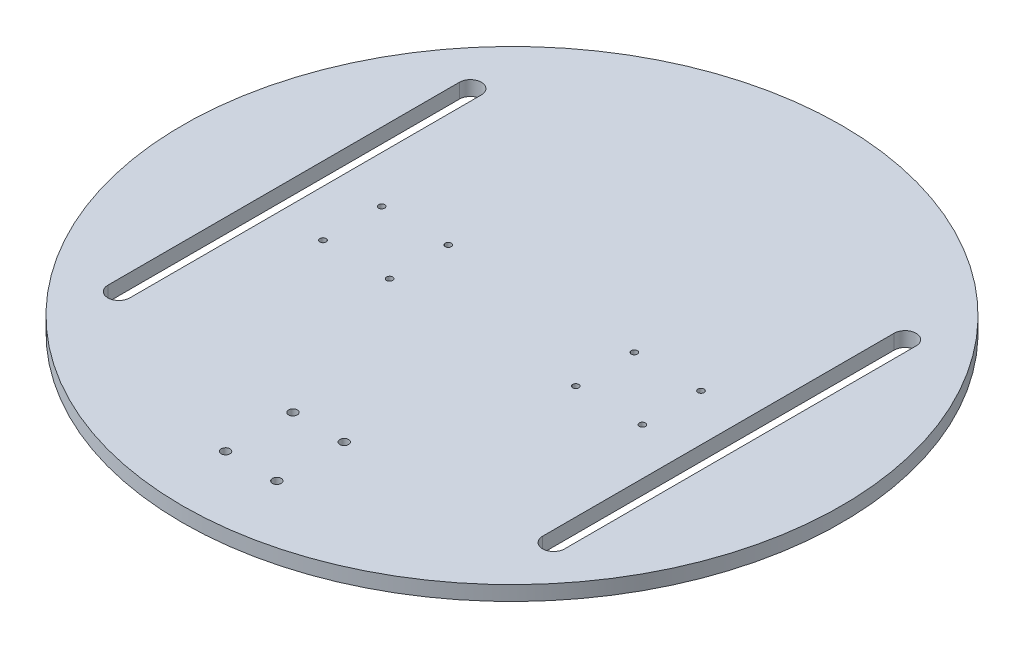
SolidWorks part; units mm, degrees
ref_plane "Front Plane" through (0, 0, 0) normal (0, 0, 1) x (1, 0, 0)
ref_plane "Top Plane" through (0, 0, 0) normal (0, 1, 0) x (1, 0, 0)
ref_plane "Right Plane" through (0, 0, 0) normal (1, 0, 0) x (0, 0, -1)
sketch "Sketch1" plane through (0, 0, 0) normal (0, 1, 0) x (1, 0, 0)
  line L0 (0, 225) -> (0, -225) construction
  line L1 (-225, 0) -> (225, 0) construction
  line L2 (-148.4069, 120) -> (-148.4069, -120) construction
  line L3 (-148.4069, -120) -> (-148.4069, 120) construction
  line L4 (-155.9069, -120) -> (-155.9069, 120)
  line L5 (-140.9069, -120) -> (-140.9069, 120)
  line L6 (148.4069, -120) -> (148.4069, 120) construction
  line L7 (155.9069, -120) -> (155.9069, 120)
  line L8 (140.9069, -120) -> (140.9069, 120)
  circle A0 centre (0, 0) radius 225
  circle A1 centre (-17.5, -132.051) radius 3
  circle A2 centre (17.5, -132.051) radius 3
  circle A3 centre (17.5, -178.051) radius 3
  circle A4 centre (-17.5, -178.051) radius 3
  arc A5 (-155.9069, -120) -> (-140.9069, -120) centre (-148.4069, -120) ccw
  arc A6 (-140.9069, 120) -> (-155.9069, 120) centre (-148.4069, 120) ccw
  arc A7 (155.9069, -120) -> (140.9069, -120) centre (148.4069, -120) cw
  arc A8 (140.9069, 120) -> (155.9069, 120) centre (148.4069, 120) cw
  point P5 (0, -155.051)
  point P18 (-148.4069, 0)
  point P19 (-148.4069, 0)
  point P21 (-148.4069, 0)
  point P28 (148.4069, 0)
  dimension "D1" = 450
  dimension "D4" = 6
  dimension "D2" = 240
  dimension "D3" = 15
extrude "Boss-Extrude1" add sketch "Sketch1" along normal blind 10
sketch "Sketch3" plane through (0, 10, 0) normal (0, 1, 0) x (1, 0, 0)
  line L0 (-225, 0) -> (225, 0) construction
  line L1 (-140.9069, -120) -> (-140.9069, 120) construction
  line L2 (0, 123.814) -> (0, -115.3201) construction
  line L5 (-129.9069, -42.9449) -> (-129.9069, 42.9449)
  circle A0 centre (0, 0) radius 225 construction
  circle A1 centre (-109.0345, -20) radius 2.1
  circle A2 centre (-63.533, -20) radius 2.1
  circle A3 centre (-63.533, 20) radius 2.1
  circle A4 centre (-109.0345, 20) radius 2.1
  circle A5 centre (109.0345, -20) radius 2.1
  circle A6 centre (63.533, -20) radius 2.1
  circle A7 centre (109.0345, 20) radius 2.1
  circle A8 centre (63.533, 20) radius 2.1
  point P5 (-86.2837, 0)
  dimension "D3" = 4.2
  dimension "D1" = 11
extrude "Cut-Extrude2" cut sketch "Sketch3" against normal blind 10 contours A6 | A8 | A2 | A1 | A3 | A4 | A5 | A7
